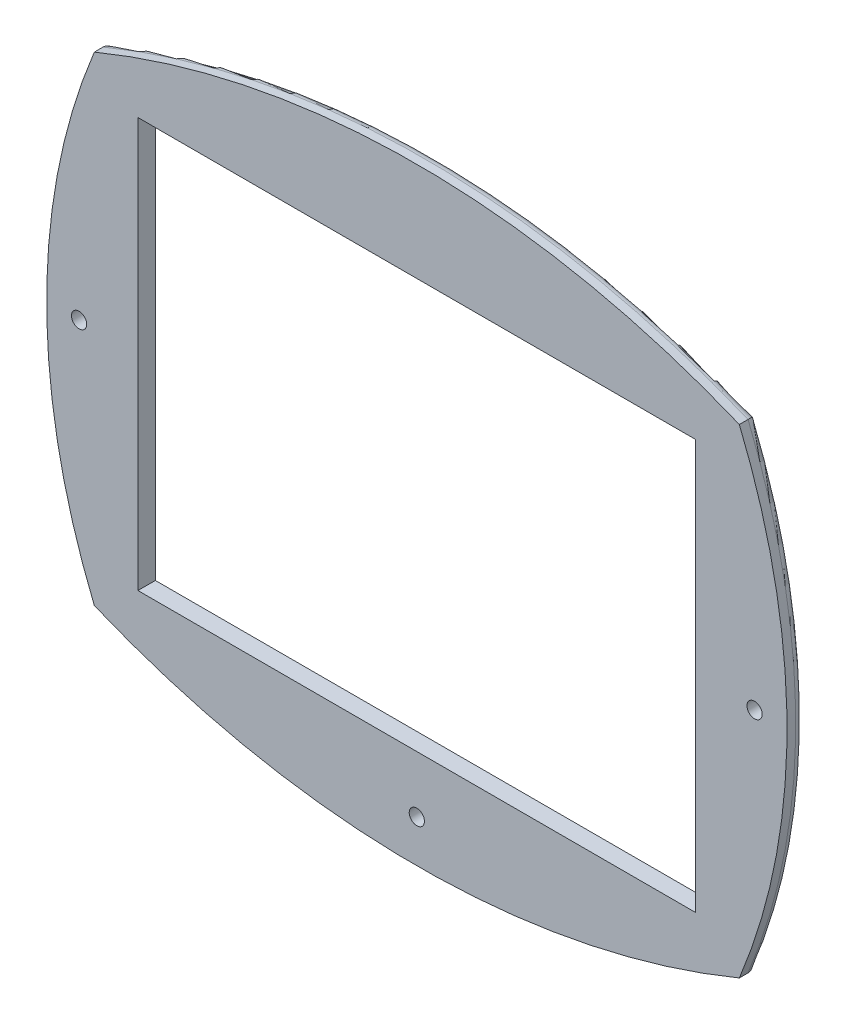
SolidWorks part; units mm, degrees
ref_plane "Front Plane" through (0, 0, 0) normal (0, 0, 1) x (1, 0, 0)
ref_plane "Top Plane" through (0, 0, 0) normal (0, 1, 0) x (1, 0, 0)
ref_plane "Right Plane" through (0, 0, 0) normal (1, 0, 0) x (0, 0, -1)
sketch "Sketch1" plane through (0, 0, 0) normal (0, 0, 1) x (1, 0, 0)
  line L1 (0, 34.8598) -> (0, -34.8598) construction
  line L2 (-32, 23.5) -> (32, 23.5)
  line L3 (-32, 23.5) -> (-32, -23.5)
  line L4 (-32, -23.5) -> (32, -23.5)
  line L5 (32, 23.5) -> (32, -23.5)
  line L6 (-32, 23.5) -> (32, -23.5) construction
  line L7 (-32, -23.5) -> (32, 23.5) construction
  arc A0 (-37, 27.5) -> (37, 27.5) centre (0, -61.8259) cw
  arc A1 (-37, 27.5) -> (-37, -27.5) centre (29.3909, 0) ccw
  arc A2 (-37, -27.5) -> (37, -27.5) centre (0, 61.8259) ccw
  arc A3 (37, 27.5) -> (37, -27.5) centre (-29.3909, 0) cw
  arc A4 (36, -25.5) -> (-36, -25.5) centre (0, 65.6482) cw
  arc A5 (-36, 25.5) -> (-36, -25.5) centre (34.5319, 0) ccw
  arc A6 (-36, 25.5) -> (36, 25.5) centre (0, -65.6482) cw
  arc A7 (36, -25.5) -> (36, 25.5) centre (-34.5319, 0) ccw
  point P1 (-37, -27.5)
  point P2 (37, -27.5)
  point P3 (-37, 27.5)
  point P4 (37, 27.5)
  point P5 (0, 0)
  point P15 (-42.4701, 0)
  point P16 (42.4701, 0)
  point P17 (0, -34.8598)
  point P18 (0, 34.8598)
  point P19 (0, 0)
  dimension "D5" = 47
  dimension "D1" = 72
  dimension "D2" = 51
  dimension "D3" = 55
  dimension "D4" = 74
  dimension "D6" = 64
extrude "Boss-Extrude1" add sketch "Sketch1" along normal blind 2 contours A4 A7 A6 A5 L2 L5 L4 L3 | A3 A0 A1 A2 A7 A4 A5 A6
fillet "Fillet1" radius 1 4 edges at (-42.4701, 0, 0) (0, -34.8598, 0) (42.4701, 0, 0) (0, 34.8598, 0)
sketch "Sketch2" plane through (0, 0, 0) normal (0, 0, -1) x (-1, 0, 0)
  line L0 (32, 23.5) -> (32, -23.5) construction
  line L1 (-32, 23.5) -> (-32, -23.5) construction
  line L2 (32, -23.5) -> (-32, -23.5) construction
  circle A0 centre (-38.75, 0) radius 0.875
  circle A1 centre (0, -30) radius 0.875
  circle A2 centre (38.75, 0) radius 0.875
  arc A3 (36.2335, -26.7341) -> (36.2335, 26.7341) centre (-29.3909, 0) ccw construction
  arc A4 (-36.2335, 26.7341) -> (-36.2335, -26.7341) centre (29.3909, 0) ccw construction
  dimension "D1" = 6.75
  dimension "D3" = 1.75
  dimension "D4" = 1.75
  dimension "D5" = 1.75
  dimension "D2" = 6.75
  dimension "D6" = 6.5
extrude "Cut-Extrude1" cut sketch "Sketch2" against normal through all
